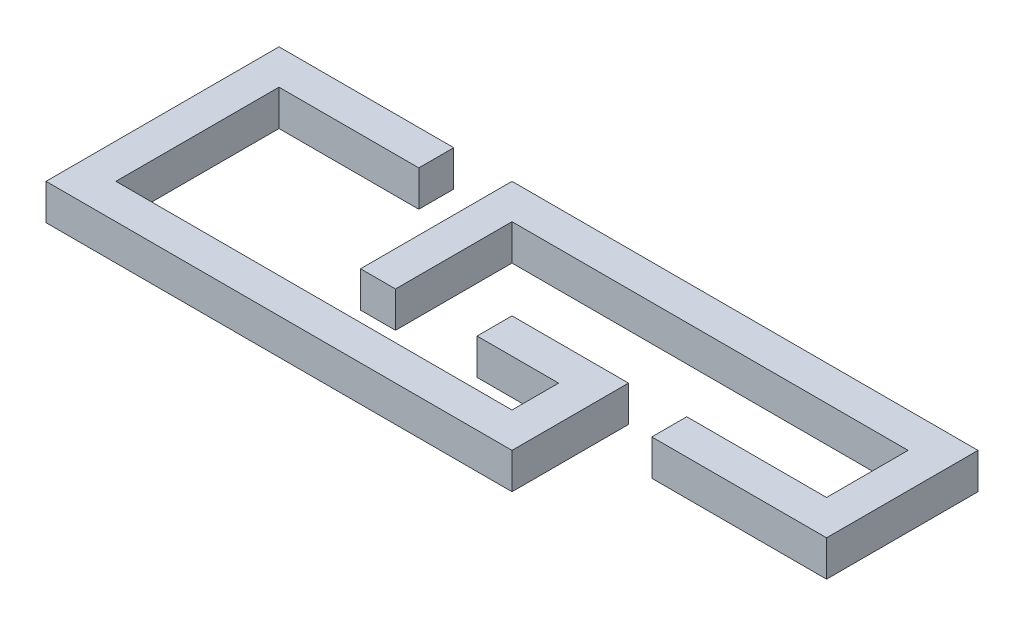
SolidWorks part; units mm, degrees
ref_plane "Front Plane" through (0, 0, 0) normal (0, 0, 1) x (1, 0, 0)
ref_plane "Top Plane" through (0, 0, 0) normal (0, 1, 0) x (1, 0, 0)
ref_plane "Right Plane" through (0, 0, 0) normal (1, 0, 0) x (0, 0, -1)
sketch "Sketch1" plane through (0, 0, 0) normal (0, 1, 0) x (1, 0, 0)
  line L0 (-6.5, 8.45) -> (-6.5, 0)
  line L1 (-6.5, 0) -> (-4.55, 0)
  line L2 (-4.55, 0) -> (-4.55, 6.5)
  line L3 (-4.55, 6.5) -> (17.55, 6.5)
  line L4 (17.55, 6.5) -> (17.55, 1.95)
  line L5 (17.55, 1.95) -> (9.75, 1.95)
  line L6 (9.75, 1.95) -> (9.75, 0)
  line L7 (9.75, 0) -> (19.5, 0)
  line L8 (19.5, 0) -> (19.5, 8.45)
  line L9 (19.5, 8.45) -> (-6.5, 8.45)
  line L10 (-19.5, 8.45) -> (-19.5, -4.55)
  line L11 (-19.5, -4.55) -> (6.5, -4.55)
  line L12 (6.5, -4.55) -> (6.5, 1.95)
  line L13 (6.5, 1.95) -> (0, 1.95)
  line L14 (0, 1.95) -> (0, 0)
  line L15 (0, 0) -> (4.55, 0)
  line L16 (4.55, 0) -> (4.55, -2.6)
  line L17 (4.55, -2.6) -> (-17.55, -2.6)
  line L18 (-17.55, -2.6) -> (-17.55, 6.5)
  line L19 (-17.55, 6.5) -> (-9.75, 6.5)
  line L20 (-9.75, 6.5) -> (-9.75, 8.45)
  line L21 (-9.75, 8.45) -> (-19.5, 8.45)
extrude "Boss-Extrude1" add sketch "Sketch1" along normal blind 2
